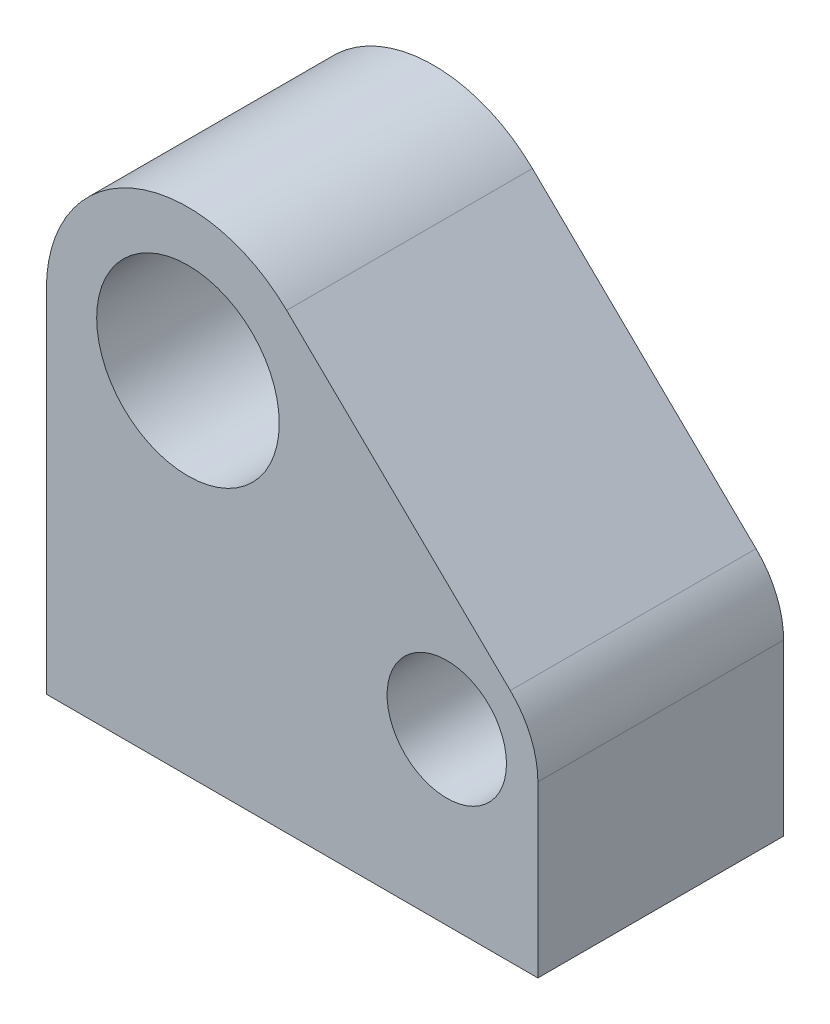
SolidWorks part; units mm, degrees
ref_plane "Alzado" through (0, 0, 0) normal (0, 0, 1) x (1, 0, 0)
ref_plane "Planta" through (0, 0, 0) normal (0, 1, 0) x (1, 0, 0)
ref_plane "Vista lateral" through (0, 0, 0) normal (1, 0, 0) x (0, 0, -1)
sketch "Croquis1" plane through (0, 0, 0) normal (0, 0, 1) x (1, 0, 0)
  line L0 (0, 0) -> (2.1298, -1.4913) construction
  line L1 (2.8112, 2.8915) -> (9.1812, -3.3017)
  line L2 (-4.0328, 0) -> (-4.0328, -10)
  line L3 (9.9672, -5.1622) -> (9.9672, -10)
  line L4 (9.9672, -10) -> (-4.0328, -10)
  line L5 (5.9798, -4.1871) -> (7.3724, -5.1622) construction
  circle A0 centre (0, 0) radius 2.6
  circle A1 centre (7.3724, -5.1622) radius 1.7
  arc A2 (2.8112, 2.8915) -> (-4.0328, 0) centre (0, 0) ccw
  arc A3 (9.9672, -5.1622) -> (9.1812, -3.3017) centre (7.3724, -5.1622) ccw
  dimension "D3" = 3.4
  dimension "D4" = 5.2
  dimension "D1" = 14
  dimension "D2" = 9
  dimension "D5" = 10
extrude "Saliente-Extruir1" add sketch "Croquis1" along normal blind 7
